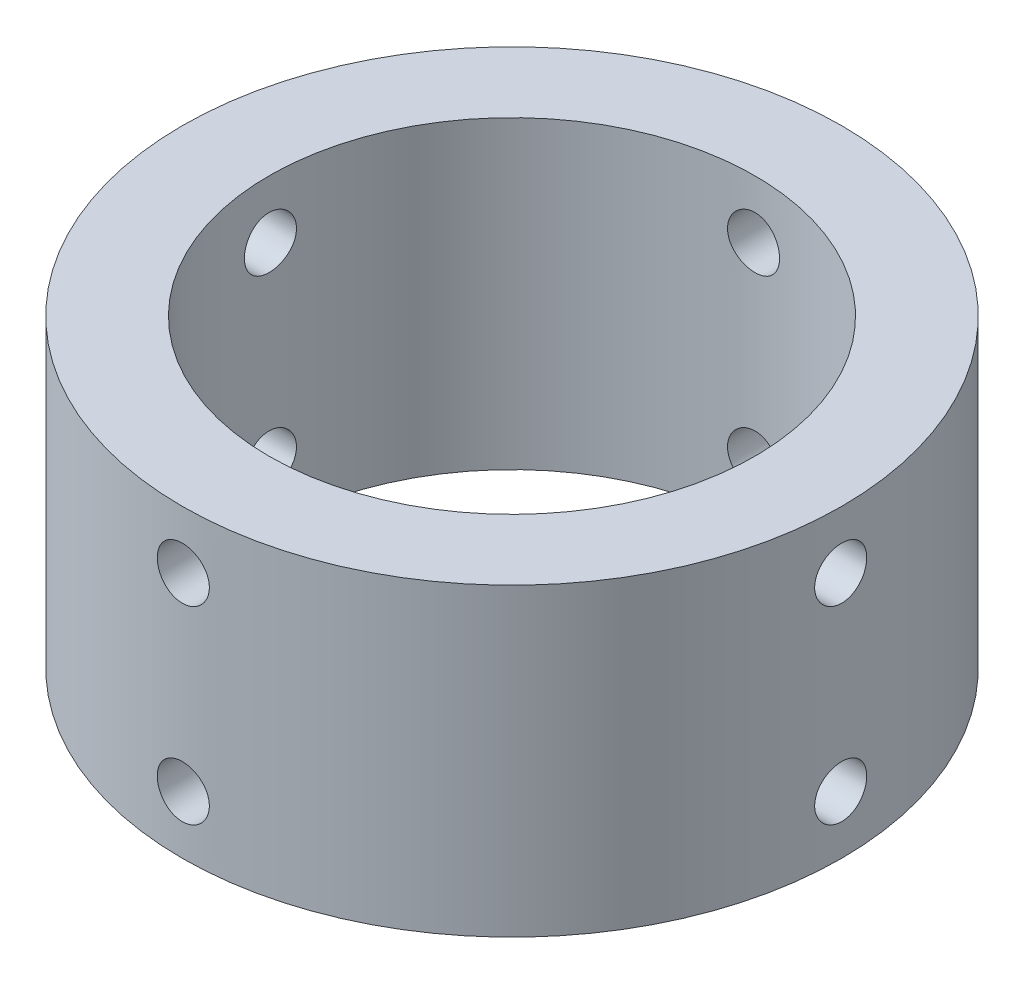
SolidWorks part; units mm, degrees
ref_plane "Front Plane" through (0, 0, 0) normal (0, 0, 1) x (1, 0, 0)
ref_plane "Top Plane" through (0, 0, 0) normal (0, 1, 0) x (1, 0, 0)
ref_plane "Right Plane" through (0, 0, 0) normal (1, 0, 0) x (0, 0, -1)
sketch "Sketch1" plane through (0, 0, 0) normal (0, 1, 0) x (1, 0, 0)
  circle A0 centre (0, 0) radius 28.5
  circle A1 centre (0, 0) radius 21
  dimension "D1" = 57
  dimension "D2" = 42
extrude "Boss-Extrude1" add sketch "Sketch1" along normal mid plane 26.35
sketch "Sketch2" plane through (0, 0, 0) normal (0, 0, 1) x (1, 0, 0)
  line L0 (-28.5, 0) -> (28.5, 0) construction
  line L1 (-28.5, 13.175) -> (-28.5, -13.175) construction
  line L2 (28.5, -13.175) -> (28.5, 13.175) construction
  circle A0 centre (0, 8.175) radius 2.25
  circle A1 centre (0, -8.175) radius 2.25
  dimension "D1" = 4.5
  dimension "D2" = 16.35
extrude "Cut-Extrude1" cut sketch "Sketch2" against normal through all
pattern_circular "CirPattern1" count 4 every 90 about axis through (0, 13.175, 0) along (0, -1, 0) of "Cut-Extrude1"
